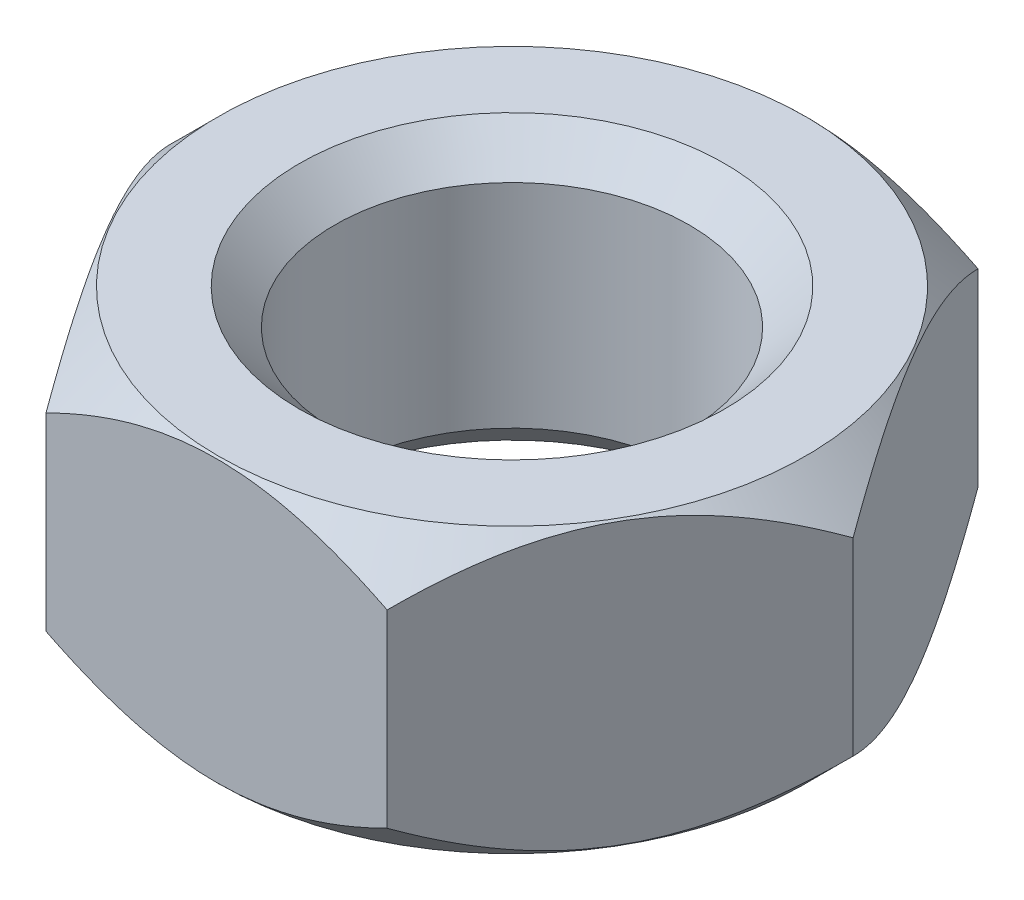
SolidWorks part; units mm, degrees
ref_plane "Спереди" through (0, 0, 0) normal (0, 0, 1) x (1, 0, 0)
ref_plane "Сверху" through (0, 0, 0) normal (0, 1, 0) x (1, 0, 0)
ref_plane "Справа" through (0, 0, 0) normal (1, 0, 0) x (0, 0, -1)
sketch "Эскиз1" plane through (0, 0, 0) normal (0, 1, 0) x (1, 0, 0)
  line L0 (-1.4434, 2.5) -> (1.4434, 2.5)
  line L1 (1.4434, 2.5) -> (2.8868, 0)
  line L2 (2.8868, 0) -> (1.4434, -2.5)
  line L3 (1.4434, -2.5) -> (-1.4434, -2.5)
  line L4 (-1.4434, -2.5) -> (-2.8868, 0)
  line L5 (-2.8868, 0) -> (-1.4434, 2.5)
  dimension "D5" = 2.5
  dimension "D2" = 120
  dimension "D3" = 120
  dimension "D4" = 120
  dimension "D6" = 2.5
  dimension "D7" = 2.5
  dimension "D8" = 2.5
  dimension "D9" = 2.5
  dimension "D10" = 120
  dimension "D11" = 2.5
extrude "Вытянуть1" add sketch "Эскиз1" against normal blind 2.4
sketch "Эскиз2" plane through (0, 0, 0) normal (0, 1, 0) x (-1, 0, 0)
  circle A0 centre (0, 0) radius 1.5
  dimension "D1" = 3
extrude "Вырез-Вытянуть1" cut sketch "Эскиз2" against normal through all
chamfer "Фаска1" distance 0.3 angle 45 2 edges at (0, -2.4, 1.5) (0, 0, 1.5)
sketch "Эскиз3" plane through (0, 0, 0) normal (0, 0, 1) x (1, 0, 0)
  line L0 (-2.8868, 0) -> (-2.4868, 0)
  line L1 (-2.8868, 0) -> (-1.4434, 0) construction
  line L2 (-2.4868, 0) -> (-2.8868, -0.4)
  line L3 (-2.8868, -2.4) -> (-2.8868, 0) construction
  line L4 (-2.8868, -0.4) -> (-2.8868, 0)
  line L5 (-2.8868, -2) -> (-2.8868, -2.4)
  line L6 (-2.8868, -2.4) -> (-2.4868, -2.4)
  line L7 (-2.4868, -2.4) -> (-2.8868, -2)
  dimension "D1" = 0.4
  dimension "D2" = 0.4
  dimension "D3" = 0.4
  dimension "D4" = 0.4
ref_axis "Ось1" through (0, -0.3, 0) along (0, -1, 0)
revolve "Вырез-Повернуть1" cut sketch "Эскиз3" angle 360 about axis through (0, -0.3, 0) along (0, -1, 0)
